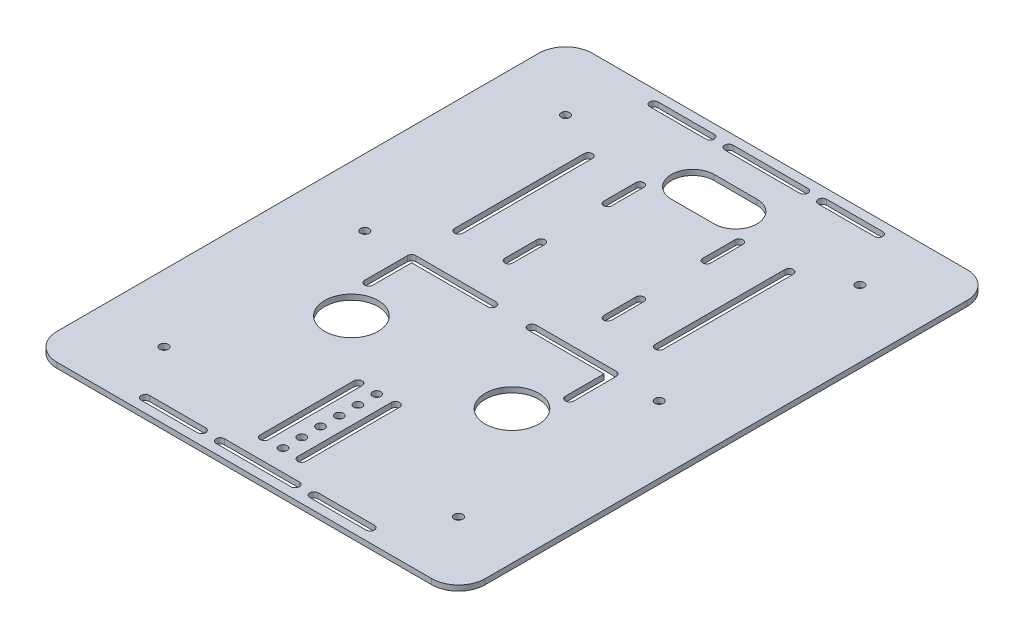
SolidWorks part; units mm, degrees
ref_plane "前视基准面" through (0, 0, 0) normal (0, 0, 1) x (1, 0, 0)
ref_plane "上视基准面" through (0, 0, 0) normal (0, 1, 0) x (1, 0, 0)
ref_plane "右视基准面" through (0, 0, 0) normal (1, 0, 0) x (0, 0, -1)
ref_plane "基准面4" through (0, 0, 0) normal (0, -1, 0) x (1, 0, 0)
sketch "草图1" plane through (0, 0, 0) normal (0, -1, 0) x (1, 0, 0)
  line L0 (37.5, -1.55) -> (7.5, -1.55)
  line L1 (7.5, 1.55) -> (35.95, 1.55)
  line L2 (35.95, 1.55) -> (35.95, 16)
  line L3 (39.05, 16) -> (39.05, 0)
  line L4 (-35.95, 1.55) -> (-35.95, 16)
  line L5 (-39.05, 16) -> (-39.05, 0)
  line L6 (-7.5, 1.55) -> (-35.95, 1.55)
  line L7 (-37.5, -1.55) -> (-7.5, -1.55)
  line L8 (39.05, -66) -> (39.05, -17.55)
  line L9 (35.95, -17.55) -> (35.95, -66)
  line L14 (-35.95, -17.55) -> (-35.95, -66)
  line L15 (-39.05, -66) -> (-39.05, -17.55)
  line L16 (8, -83.55) -> (-8, -83.55)
  line L17 (-8, -67.55) -> (8, -67.55)
  line L18 (8.55, 85.5527) -> (8.55, 50.5527)
  line L19 (5.45, 50.5527) -> (5.45, 85.5527)
  line L20 (-8.55, 50.5527) -> (-8.55, 85.5527)
  line L21 (-5.45, 85.5527) -> (-5.45, 50.5527)
  line L22 (42, 93.45) -> (21, 93.45)
  line L23 (21, 96.55) -> (42, 96.55)
  line L24 (-21, 93.45) -> (-42, 93.45)
  line L25 (-42, 96.55) -> (-21, 96.55)
  line L26 (14, 93.45) -> (-14, 93.45)
  line L27 (-14, 96.55) -> (14, 96.55)
  line L28 (21, -93.45) -> (42, -93.45)
  line L29 (42, -96.55) -> (21, -96.55)
  line L30 (-42, -93.45) -> (-21, -93.45)
  line L31 (-21, -96.55) -> (-42, -96.55)
  line L32 (-14, -93.45) -> (14, -93.45)
  line L33 (14, -96.55) -> (-14, -96.55)
  line L34 (-70, -100) -> (70, -100)
  line L35 (80, -90) -> (80, 90)
  line L36 (70, 100) -> (-70, 100)
  line L37 (-80, 90) -> (-80, -90)
  line L38 (0, 100) -> (0, -100) construction
  line L39 (-55, 75) -> (55, 75) construction
  line L40 (55, 75) -> (55, -75) construction
  line L41 (55, -75) -> (-55, -75) construction
  line L42 (-55, -75) -> (-55, 75) construction
  line L43 (-80, 0) -> (80, 0) construction
  arc A0 (7.5, -1.55) -> (7.5, 1.55) centre (7.5, 0) cw
  arc A1 (35.95, 16) -> (39.05, 16) centre (37.5, 16) cw
  arc A2 (39.05, 0) -> (37.5, -1.55) centre (37.5, 0) cw
  arc A3 (-35.95, 16) -> (-39.05, 16) centre (-37.5, 16) ccw
  arc A4 (-39.05, 0) -> (-37.5, -1.55) centre (-37.5, 0) ccw
  arc A5 (-7.5, -1.55) -> (-7.5, 1.55) centre (-7.5, 0) ccw
  arc A6 (35.95, -66) -> (39.05, -66) centre (37.5, -66) ccw
  arc A7 (39.05, -17.55) -> (35.95, -17.55) centre (37.5, -17.55) ccw
  arc A12 (-39.05, -17.55) -> (-35.95, -17.55) centre (-37.5, -17.55) cw
  arc A13 (-35.95, -66) -> (-39.05, -66) centre (-37.5, -66) cw
  arc A14 (-8, -83.55) -> (-8, -67.55) centre (-8, -75.55) cw
  arc A15 (8, -67.55) -> (8, -83.55) centre (8, -75.55) cw
  arc A16 (8.55, 50.5527) -> (5.45, 50.5527) centre (7, 50.5527) cw
  arc A17 (5.45, 85.5527) -> (8.55, 85.5527) centre (7, 85.5527) cw
  arc A18 (-5.45, 50.5527) -> (-8.55, 50.5527) centre (-7, 50.5527) cw
  arc A19 (-8.55, 85.5527) -> (-5.45, 85.5527) centre (-7, 85.5527) cw
  circle A20 centre (0, 50.5527) radius 1.55
  circle A21 centre (0, 57.5527) radius 1.55
  circle A22 centre (0, 64.5527) radius 1.55
  circle A23 centre (0, 71.5527) radius 1.55
  circle A24 centre (0, 78.5527) radius 1.55
  circle A25 centre (0, 85.5527) radius 1.55
  arc A26 (42, 96.55) -> (42, 93.45) centre (42, 95) cw
  arc A27 (21, 93.45) -> (21, 96.55) centre (21, 95) cw
  arc A28 (-42, 93.45) -> (-42, 96.55) centre (-42, 95) cw
  arc A29 (-21, 96.55) -> (-21, 93.45) centre (-21, 95) cw
  arc A30 (-14, 93.45) -> (-14, 96.55) centre (-14, 95) cw
  arc A31 (14, 96.55) -> (14, 93.45) centre (14, 95) cw
  circle A32 centre (-30, 30) radius 10
  circle A33 centre (30, 30) radius 10
  arc A34 (42, -93.45) -> (42, -96.55) centre (42, -95) cw
  arc A35 (21, -96.55) -> (21, -93.45) centre (21, -95) cw
  arc A36 (-42, -96.55) -> (-42, -93.45) centre (-42, -95) cw
  arc A37 (-21, -93.45) -> (-21, -96.55) centre (-21, -95) cw
  arc A38 (-14, -96.55) -> (-14, -93.45) centre (-14, -95) cw
  arc A39 (14, -93.45) -> (14, -96.55) centre (14, -95) cw
  circle A40 centre (55, 75) radius 1.6
  circle A41 centre (55, 0) radius 1.6
  circle A42 centre (55, -75) radius 1.6
  circle A43 centre (-55, -75) radius 1.6
  circle A44 centre (-55, 0) radius 1.6
  circle A45 centre (-55, 75) radius 1.6
  arc A46 (-80, -90) -> (-70, -100) centre (-70, -90) ccw
  arc A47 (70, -100) -> (80, -90) centre (70, -90) ccw
  arc A48 (80, 90) -> (70, 100) centre (70, 90) ccw
  arc A49 (-70, 100) -> (-80, 90) centre (-70, 90) ccw
  dimension "D7" = 10
  dimension "D8" = 20
  dimension "D9" = 60
  dimension "D10" = 30
  dimension "D11" = 21
  dimension "D14" = 21
  dimension "D17" = 28
  dimension "D20" = 16
  dimension "D23" = 3.2
  dimension "D25" = 3.2
  dimension "D28" = 28.45
  dimension "D29" = 14.45
  dimension "D18" = 75
  dimension "D33" = 75
  dimension "D1" = 160
  dimension "D2" = 200
  dimension "D3" = 100
  dimension "D4" = 80
  dimension "D5" = 140
  dimension "D6" = 180
  dimension "D12" = 3.1
  dimension "D13" = 3.45
  dimension "D15" = 21
  dimension "D16" = 21
  dimension "D19" = 16.45
  dimension "D21" = 150
  dimension "D22" = 110
  dimension "D24" = 75
  dimension "D26" = 3.1
  dimension "D27" = 3.1
  dimension "D30" = 30
  dimension "D31" = 3.1
  dimension "D32" = 48.45
  dimension "D34" = 34
  dimension "D35" = 16
extrude "凸台-拉伸1" add sketch "草图1" against normal blind 2
sketch "草图2" plane through (0, 0, 0) normal (0, -1, 0) x (1, 0, 0)
  line L0 (-18.5, -17.275) -> (-18.5, -29.275) construction
  line L1 (-17, -17.275) -> (-17, -29.275)
  line L2 (-20, -17.275) -> (-20, -29.275)
  line L3 (-18.5, -54.275) -> (-18.5, -66.275) construction
  line L4 (-17, -54.275) -> (-17, -66.275)
  line L5 (-20, -54.275) -> (-20, -66.275)
  line L6 (0, -100) -> (0, 100) construction
  line L7 (-70, -100) -> (70, -100) construction
  line L8 (70, 100) -> (-70, 100) construction
  line L9 (18.5, -54.275) -> (18.5, -66.275) construction
  line L10 (17, -54.275) -> (17, -66.275)
  line L11 (20, -54.275) -> (20, -66.275)
  line L12 (18.5, -17.275) -> (18.5, -29.275) construction
  line L13 (17, -17.275) -> (17, -29.275)
  line L14 (20, -17.275) -> (20, -29.275)
  line L15 (-35.95, -41.775) -> (35.95, -41.775) construction
  line L16 (-35.95, -66) -> (-35.95, -17.55) construction
  line L17 (35.95, -17.55) -> (35.95, -66) construction
  arc A0 (-17, -17.275) -> (-20, -17.275) centre (-18.5, -17.275) ccw
  arc A1 (-20, -29.275) -> (-17, -29.275) centre (-18.5, -29.275) ccw
  arc A2 (-17, -54.275) -> (-20, -54.275) centre (-18.5, -54.275) ccw
  arc A3 (-20, -66.275) -> (-17, -66.275) centre (-18.5, -66.275) ccw
  arc A4 (17, -54.275) -> (20, -54.275) centre (18.5, -54.275) cw
  arc A5 (20, -66.275) -> (17, -66.275) centre (18.5, -66.275) cw
  arc A6 (17, -17.275) -> (20, -17.275) centre (18.5, -17.275) cw
  arc A7 (20, -29.275) -> (17, -29.275) centre (18.5, -29.275) cw
  point P2 (-18.5, -23.275)
  point P8 (-18.5, -60.275)
  point P22 (18.5, -60.275)
  point P29 (18.5, -23.275)
  dimension "D1" = 3
  dimension "D2" = 12
  dimension "D3" = 37
  dimension "D4" = 37
extrude "切除-拉伸1" cut sketch "草图2" against normal blind 10
